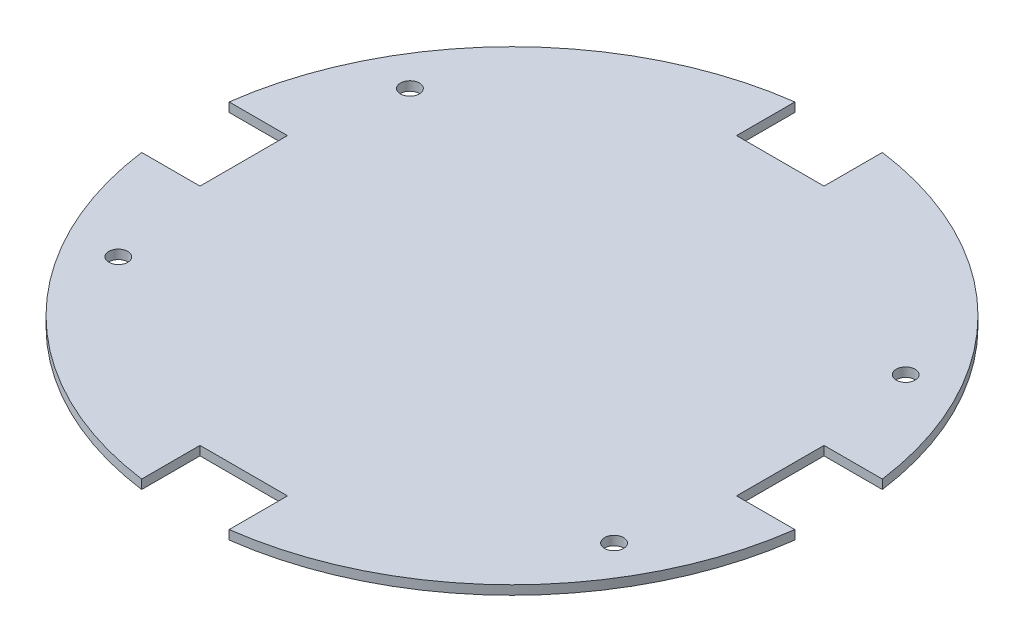
SolidWorks part; units mm, degrees
ref_plane "Front Plane" through (0, 0, 0) normal (0, 0, 1) x (1, 0, 0)
ref_plane "Top Plane" through (0, 0, 0) normal (0, 1, 0) x (1, 0, 0)
ref_plane "Right Plane" through (0, 0, 0) normal (1, 0, 0) x (0, 0, -1)
sketch "Sketch1" plane through (0, 0, 0) normal (0, 1, 0) x (1, 0, 0)
  line L4 (-7.62, 56.896) -> (-7.62, 46.736)
  line L5 (-7.62, 46.736) -> (7.62, 46.736)
  line L6 (7.62, 46.736) -> (7.62, 56.896)
  line L7 (56.896, 7.62) -> (46.736, 7.62)
  line L8 (46.736, 7.62) -> (46.736, -7.62)
  line L9 (46.736, -7.62) -> (56.896, -7.62)
  line L10 (-56.896, 7.62) -> (-46.736, 7.62)
  line L11 (-46.736, 7.62) -> (-46.736, -7.62)
  line L12 (-46.736, -7.62) -> (-56.896, -7.62)
  line L13 (-7.62, -56.896) -> (-7.62, -46.736)
  line L14 (-7.62, -46.736) -> (7.62, -46.736)
  line L15 (7.62, -46.736) -> (7.62, -56.896)
  circle A1 centre (-43.18, 25.4) radius 1.651
  circle A2 centre (-43.18, -25.4) radius 1.651
  circle A3 centre (43.18, -25.4) radius 1.651
  circle A4 centre (43.18, 25.4) radius 1.651
  arc A5 (-7.62, 56.896) -> (-56.896, 7.62) centre (0, 0) ccw
  arc A6 (56.896, 7.62) -> (7.62, 56.896) centre (0, 0) ccw
  arc A7 (-56.896, -7.62) -> (-7.62, -56.896) centre (0, 0) ccw
  arc A8 (7.62, -56.896) -> (56.896, -7.62) centre (0, 0) ccw
  point P32 (0, 46.736)
  point P33 (46.736, 0)
  dimension "D2" = 3.302
  dimension "D3" = 3.302
  dimension "D4" = 3.302
  dimension "D5" = 3.302
  dimension "D6" = 25.4
  dimension "D7" = 43.18
  dimension "D8" = 43.18
  dimension "D9" = 25.4
  dimension "D10" = 15.24
  dimension "D11" = 10.16
  dimension "D12" = 10.16
  dimension "D13" = 15.24
  dimension "D14" = 10.16
  dimension "D15" = 10.16
extrude "Boss-Extrude1" add sketch "Sketch1" along normal blind 1.5875
